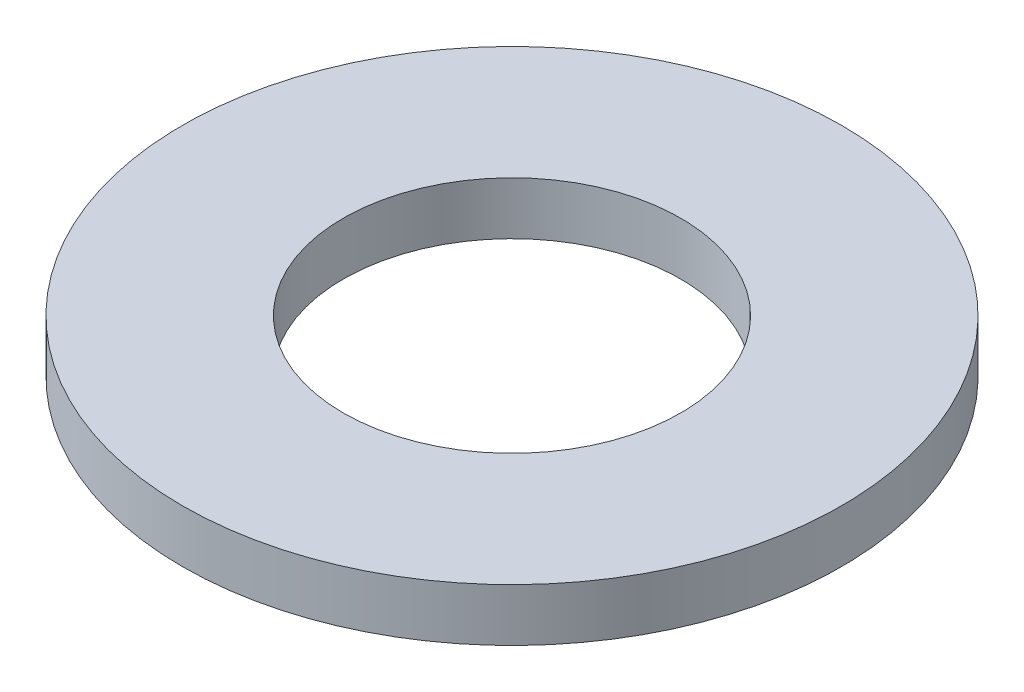
SolidWorks part; units mm, degrees
material "Stainless Steel (ferritic)"
ref_plane "Front Plane" through (0, 0, 0) normal (0, 0, 1) x (1, 0, 0)
ref_plane "Top Plane" through (0, 0, 0) normal (0, 1, 0) x (1, 0, 0)
ref_plane "Right Plane" through (0, 0, 0) normal (1, 0, 0) x (0, 0, -1)
sketch "Sketch1" plane through (0, 0, 0) normal (0, 1, 0) x (1, 0, 0)
  circle A0 centre (0, 0) radius 3.2
  circle A1 centre (0, 0) radius 6.25
  dimension "D1" = 6.4
  dimension "D2" = 12.5
extrude "Boss-Extrude1" add sketch "Sketch1" along normal blind 1
